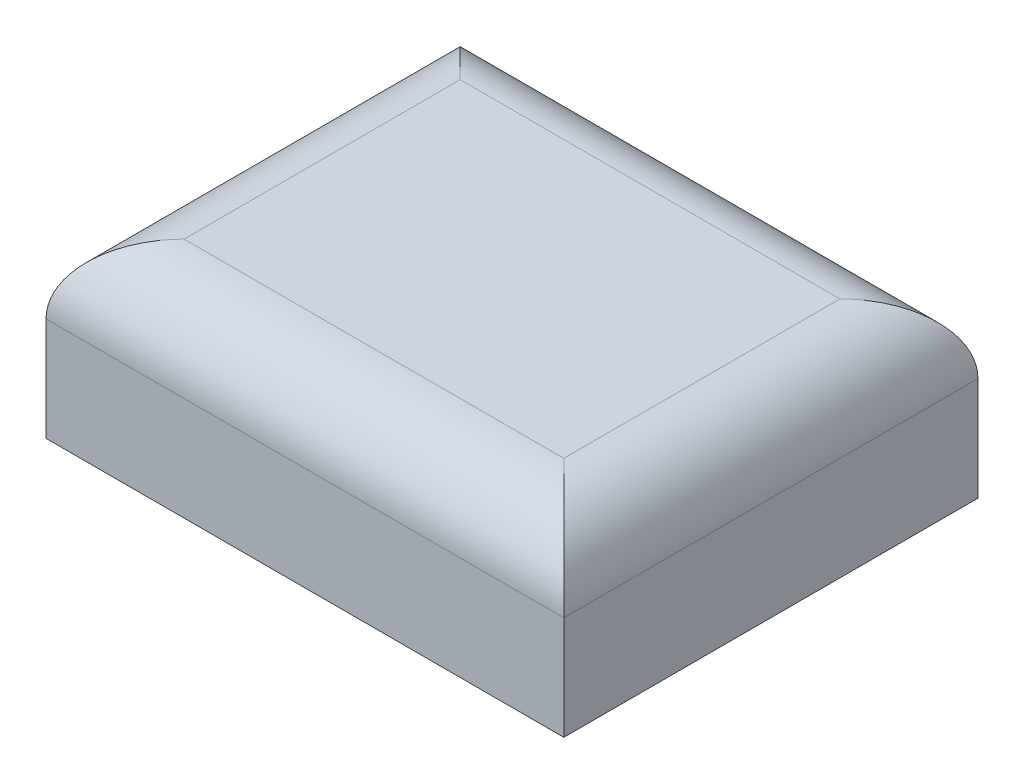
SolidWorks part; units mm, degrees
ref_plane "Front Plane" through (0, 0, 0) normal (0, 0, 1) x (1, 0, 0)
ref_plane "Top Plane" through (0, 0, 0) normal (0, 1, 0) x (1, 0, 0)
ref_plane "Right Plane" through (0, 0, 0) normal (1, 0, 0) x (0, 0, -1)
sketch "Sketch1" plane through (0, 0, 0) normal (0, 1, 0) x (1, 0, 0)
  line L1 (-75, 60) -> (75, 60)
  line L2 (-75, 60) -> (-75, -60)
  line L3 (-75, -60) -> (75, -60)
  line L4 (75, 60) -> (75, -60)
  line L5 (-75, 60) -> (75, -60) construction
  line L6 (-75, -60) -> (75, 60) construction
  point P0 (0, 0)
  dimension "D1" = 150
  dimension "D2" = 120
extrude "Boss-Extrude1" add sketch "Sketch1" along normal blind 50
fillet "Fillet1" radius 20 4 edges at (0, 50, 60) (-75, 50, 0) (0, 50, -60) (75, 50, 0)
shell "Shell1" thickness 5
sketch "Sketch2" plane through (0, 0, 0) normal (0, -1, 0) x (1, 0, 0)
  line L0 (-70, -28.6193) -> (70, -28.6193)
  line L1 (-70, 55) -> (-70, -55) construction
  line L2 (70, -55) -> (70, 55) construction
  line L3 (-70, 0) -> (70, 0)
  line L4 (70, 55) -> (70, -55) construction
  line L5 (-70, 26.7115) -> (71.4524, 26.7115)
  line L6 (-70, -55) -> (-70, 55) construction
  line L7 (0, 55) -> (0, -55)
  line L8 (-70, 55) -> (70, 55) construction
  line L9 (-70, -55) -> (70, -55) construction
  line L10 (-30.6509, 55) -> (-29.2577, -55)
  line L11 (70, 55) -> (-70, 55) construction
  line L12 (39.4083, 55) -> (39.4083, -55)
rib "Rib1" sketch "Sketch2" sketch "Sketch2" thickness 5 extrusion direction normal to sketch draft on no parameters "D1"=5
